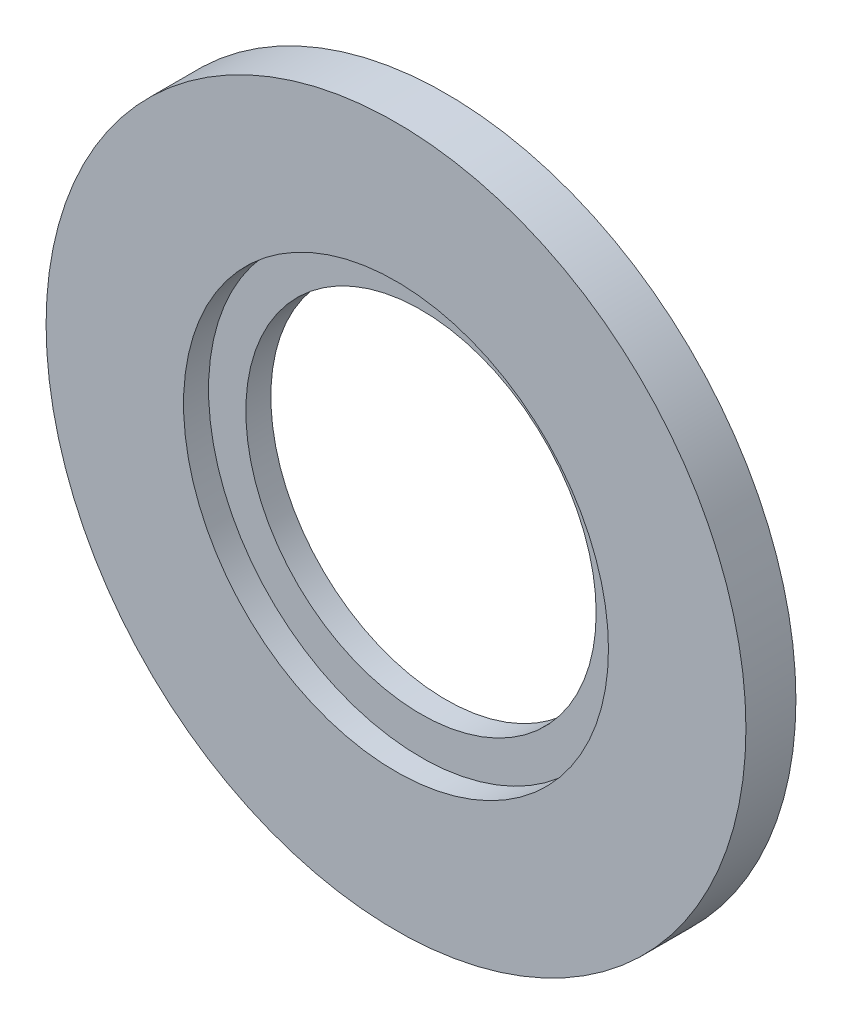
SolidWorks part; units mm, degrees
material "6061-T6 (SS)"
ref_plane "Front Plane" through (0, 0, 0) normal (0, 0, 1) x (1, 0, 0)
ref_plane "Top Plane" through (0, 0, 0) normal (0, 1, 0) x (1, 0, 0)
ref_plane "Right Plane" through (0, 0, 0) normal (1, 0, 0) x (0, 0, -1)
sketch "Sketch1" plane through (0, 0, 0) normal (0, 0, 1) x (1, 0, 0)
  circle A0 centre (0, 0) radius 22.225
  circle A1 centre (0, 0) radius 11.1252
  dimension "D1" = 44.45
  dimension "D2" = 22.2504
extrude "Boss-Extrude1" add sketch "Sketch1" along normal blind 3.175
sketch "Sketch2" plane through (0, 0, 3.175) normal (0, 0, 1) x (1, 0, 0)
  circle A0 centre (0, 0) radius 13.4938
  dimension "D1" = 26.9875
extrude "Cut-Extrude1" cut sketch "Sketch2" against normal blind 1.5875
